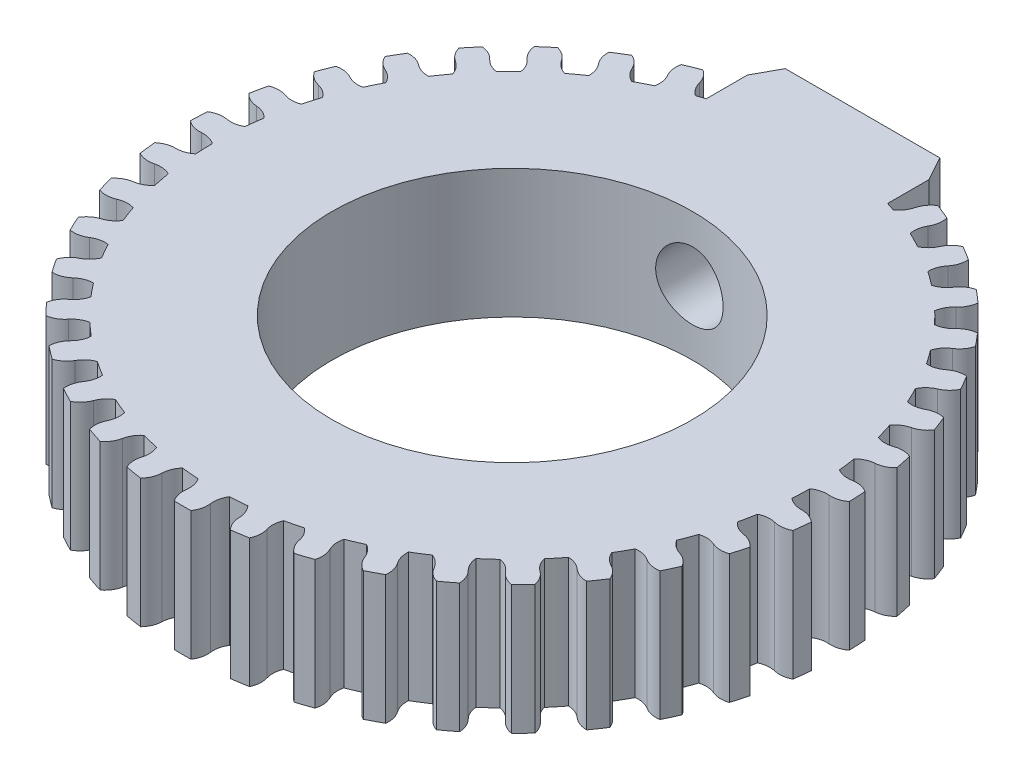
SolidWorks part; units mm, degrees
ref_plane "Front Plane" through (0, 0, 0) normal (0, 0, 1) x (1, 0, 0)
ref_plane "Top Plane" through (0, 0, 0) normal (0, 1, 0) x (1, 0, 0)
ref_plane "Right Plane" through (0, 0, 0) normal (1, 0, 0) x (0, 0, -1)
sketch "Sketch1" plane through (0, 0, 0) normal (0, 1, 0) x (1, 0, 0)
  line L0 (-2.2352, 7.0187) -> (-2.2352, 8.0347)
  line L1 (-2.2352, 8.0347) -> (-1.905, 8.636)
  line L2 (-1.905, 8.636) -> (1.905, 8.636)
  line L3 (1.905, 8.636) -> (2.2352, 8.0347)
  line L4 (2.2352, 8.0347) -> (2.2352, 7.0187)
  line L5 (-2.2352, 7.0187) -> (2.2352, 7.0187) construction
  line L6 (-2.2352, 8.0347) -> (2.2352, 8.0347) construction
  line L7 (0, 8.636) -> (0, 0) construction
  circle A0 centre (0, 0) radius 4.445
  arc A1 (-2.2352, 7.0187) -> (2.2352, 7.0187) centre (0, 0) ccw
  point P11 (0, 8.0347)
  point P12 (0, 0)
  point P13 (0, 0)
  dimension "D1" = 8.89
  dimension "D2" = 14.732
  dimension "D3" = 3.81
  dimension "D4" = 4.4704
  dimension "D5" = 8.636
  dimension "D6" = 1.016
extrude "Boss-Extrude1" add sketch "Sketch1" along normal blind 3.175
sketch "Sketch2" plane through (0, 0, -8.636) normal (0, 0, -1) x (-1, 0, 0)
  line L0 (1.905, 1.5875) -> (-1.905, 1.5875) construction
  line L1 (1.905, 3.175) -> (1.905, 0) construction
  line L2 (-1.905, 3.175) -> (-1.905, 0) construction
  line L3 (0, 0) -> (0, 3.175) construction
  line L4 (-1.905, 0) -> (1.905, 0) construction
  line L5 (-1.905, 3.175) -> (1.905, 3.175) construction
  circle A0 centre (0, 1.5875) radius 0.8318
  point P14 (0, 0)
  dimension "D1" = 1.6637
extrude "Cut-Extrude1" cut sketch "Sketch2" against normal blind 10.795
sketch "Sketch3" plane through (0, 0, 0) normal (0, -1, 0) x (1, 0, 0)
  line L0 (-2.2352, -7.0187) -> (0, 0) construction
  line L1 (0, 0) -> (2.2352, -7.0187) construction
  line L2 (-2.2352, -7.0187) -> (-2.4664, -7.7447) construction
  line L3 (-2.2352, -8.0347) -> (-2.2352, -7.0187) construction
  line L4 (0, 0) -> (-3.6825, -7.246) construction
  line L5 (-3.0845, -7.52) -> (-1.6869, -4.1125) construction
  line L6 (-2.8938, -7.5954) -> (0, 0) construction
  line L7 (-2.6879, -7.6707) -> (0, 0) construction
  circle A0 centre (0, 0) radius 8.128 construction
  arc A1 (-3.2733, -7.4397) -> (-2.8938, -7.5954) centre (0, 0) ccw
  circle A2 centre (0, 0) radius 4.445 construction
  arc A3 (-1.3488, -4.2354) -> (-2.0139, -3.9626) centre (0, 0) cw construction
  arc A4 (-2.2352, -7.0187) -> (-2.4359, -6.9516) centre (0, 0) cw construction
  arc A5 (2.2352, -7.0187) -> (-2.2352, -7.0187) centre (0, 0) ccw construction
  arc A6 (-2.8938, -7.5954) -> (-2.6571, -7.2683) centre (-3.1976, -7.1264) ccw
  arc A7 (-2.4359, -6.9516) -> (-2.6571, -7.2683) centre (-2.1166, -7.4102) ccw
  arc A8 (-3.3372, -6.5666) -> (-3.1473, -6.6598) centre (0, 0) ccw construction
  arc A9 (-3.1473, -6.6598) -> (-3.2121, -7.0406) centre (-3.6966, -6.7621) cw
  arc A10 (-3.2733, -7.4397) -> (-3.2121, -7.0406) centre (-2.7277, -7.3191) cw
  arc A11 (-2.4359, -6.9516) -> (-3.1473, -6.6598) centre (0, 0) cw
  dimension "D1" = 16.256
  dimension "D6" = 0.5588
  dimension "D7" = 0.5588
  dimension "D2" = 35.33
  dimension "D3" = 9.275
  dimension "D4" = 1.446
  dimension "D5" = 1.546
  dimension "D8" = 0.5551
extrude "Boss-Extrude2" add sketch "Sketch3" against normal up to surface (3.175 mm away) up to face at (0, 3.175, -5.499)
pattern_circular "CirPattern1" count 35 every 9.275 about axis through (0, 0, 0) along (0, 1, 0) of "Boss-Extrude2"
